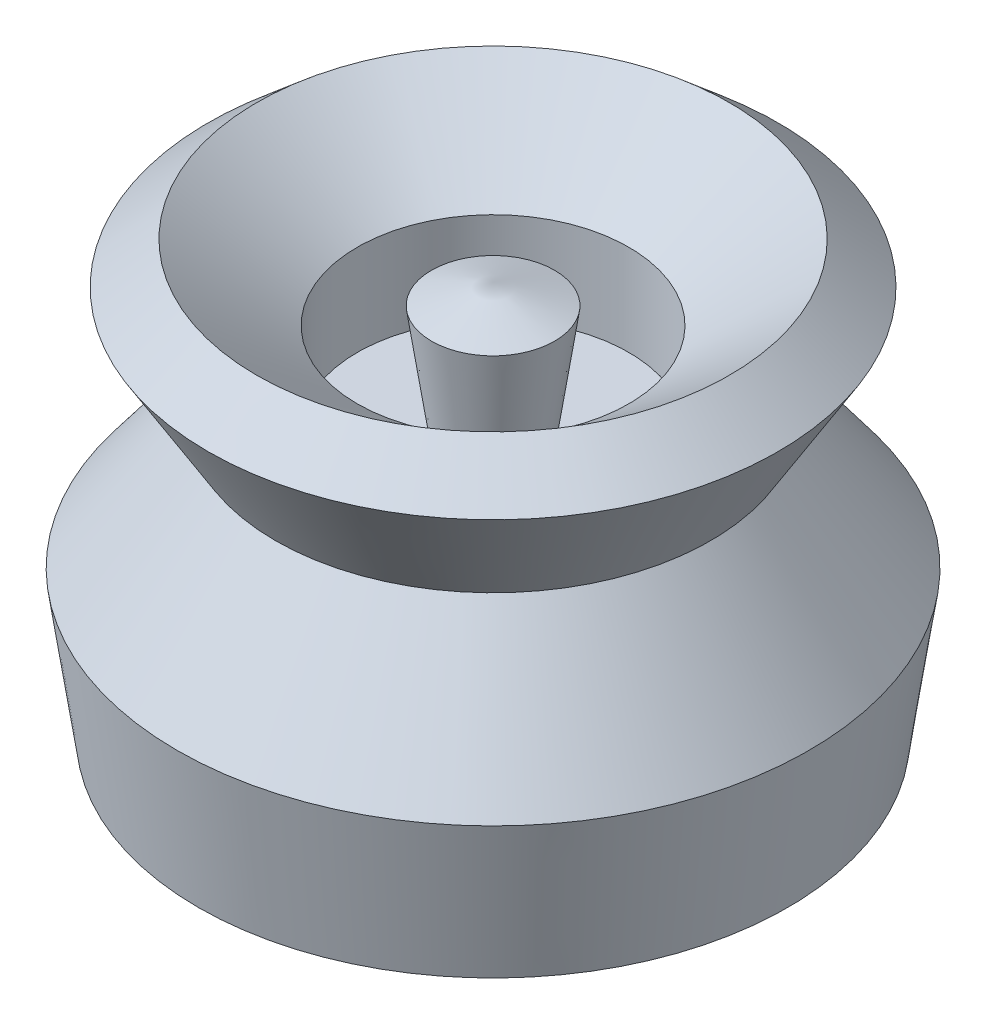
SolidWorks part; units mm, degrees
ref_plane "Front Plane" through (0, 0, 0) normal (0, 0, 1) x (1, 0, 0)
ref_plane "Top Plane" through (0, 0, 0) normal (0, 1, 0) x (1, 0, 0)
ref_plane "Right Plane" through (0, 0, 0) normal (1, 0, 0) x (0, 0, -1)
sketch "Sketch1" plane through (0, 0, 0) normal (0, 0, 1) x (1, 0, 0)
  line L0 (0, 37.4984) -> (0, -30.9277)
  line L1 (0, -30.9277) -> (68.6526, -30.9277)
  line L2 (68.6526, -30.9277) -> (73.6373, 3.2854)
  line L3 (73.6373, 3.2854) -> (50.6676, 34.0897)
  line L4 (50.6676, 34.0897) -> (66.3869, 59.9294)
  line L5 (66.3869, 59.9294) -> (55.0581, 69.6722)
  line L6 (55.0581, 69.6722) -> (31.6278, 52.2011)
  line L7 (31.6278, 52.2011) -> (31.6278, 48.8272)
  line L8 (31.6278, 30.9698) -> (10.6491, 30.9698)
  line L9 (10.6491, 30.9698) -> (14.3248, 56.1984)
  line L10 (14.3248, 56.1984) -> (0, 60.9367)
  line L11 (0, 60.9367) -> (0, 37.4984)
  line L12 (31.6278, 30.9698) -> (31.6278, 48.8272)
revolve "Revolve1" add sketch "Sketch1" angle 360 about L0
